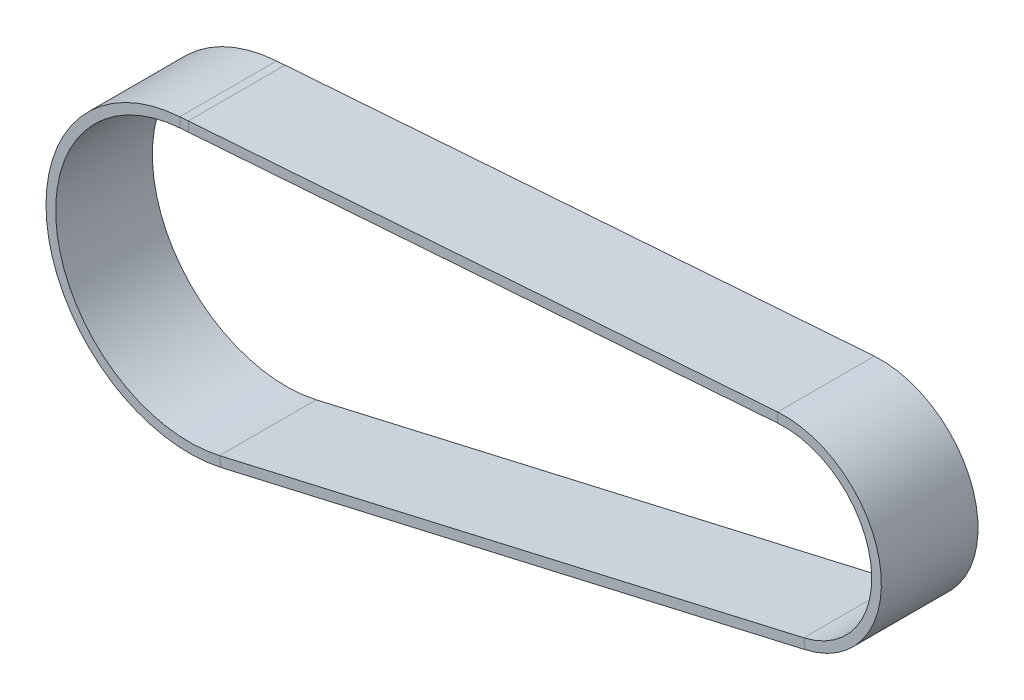
SolidWorks part; units mm, degrees
ref_plane "Alzado" through (0, 0, 0) normal (0, 0, 1) x (1, 0, 0)
ref_plane "Planta" through (0, 0, 0) normal (0, 1, 0) x (1, 0, 0)
ref_plane "Vista lateral" through (0, 0, 0) normal (1, 0, 0) x (0, 0, -1)
sketch "Croquis2" plane through (0, 0, 0) normal (0, 0, 1) x (1, 0, 0)
  line L0 (0, 0) -> (1, 0) construction
  line L1 (0, 0) -> (0, 1) construction
  line L2 (-0.8815, 11.6287) -> (60.9506, 16.1062)
  line L3 (63.6561, -1.8978) -> (3.2391, -15.7913)
  arc A0 (3.2391, -15.7913) -> (-0.8815, 11.6287) centre (0.1228, -2.24) cw
  arc A1 (60.9506, 16.1062) -> (63.6561, -1.8978) centre (61.61, 7) cw
sketch "Croquis3" plane through (0, 0, 0) normal (1, 0, 0) x (0, 0, -1)
  line L1 (-5, 12.6287) -> (5, 12.6287)
  line L2 (-5, 12.6287) -> (-5, 11.6287)
  line L3 (-5, 11.6287) -> (5, 11.6287)
  line L4 (5, 12.6287) -> (5, 11.6287)
  point P4 (0, 11.6287)
  dimension "D1" = 10
  dimension "D2" = 1
sweep "Barrer1" add profiles "Croquis3" path "Croquis2"
